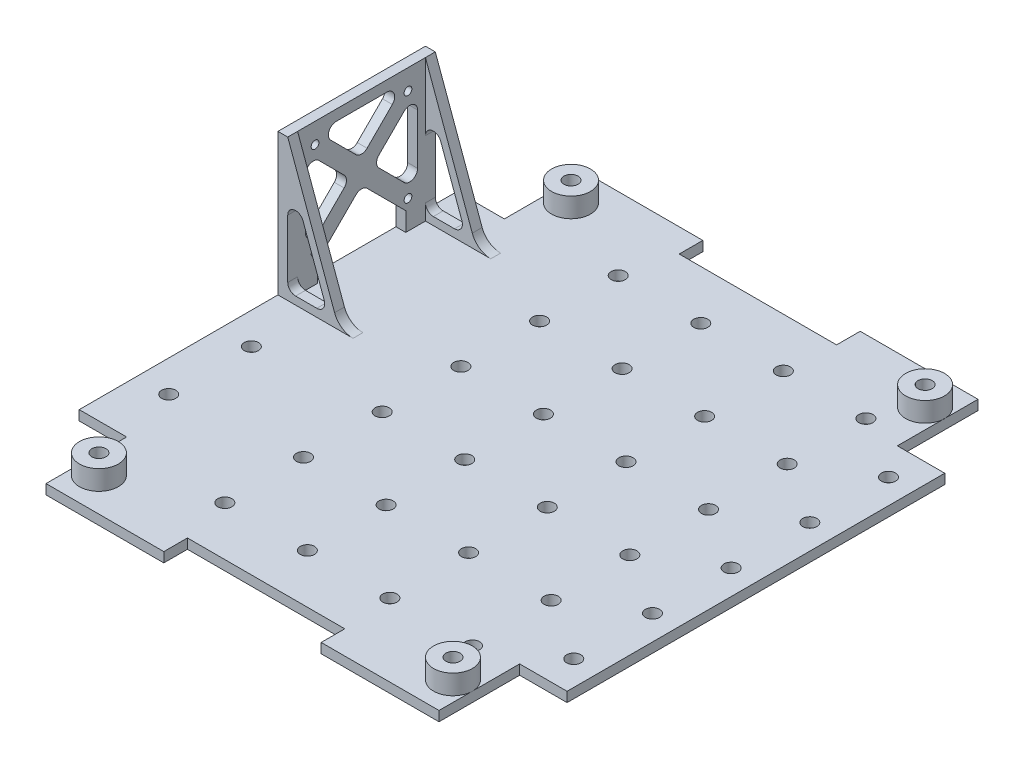
SolidWorks part; units mm, degrees
ref_plane "Front Plane" through (0, 0, 0) normal (0, 0, 1) x (1, 0, 0)
ref_plane "Top Plane" through (0, 0, 0) normal (0, 1, 0) x (1, 0, 0)
ref_plane "Right Plane" through (0, 0, 0) normal (1, 0, 0) x (0, 0, -1)
sketch "Sketch1" plane through (0, 0, 0) normal (0, 1, 0) x (1, 0, 0)
  line L0 (-25.4, 86.995) -> (-63.4314, 86.995)
  line L1 (-88.9, -101.6) -> (88.9, -101.6) construction
  line L2 (101.6, -88.9) -> (101.6, 88.9) construction
  line L3 (88.9, 101.6) -> (-88.9, 101.6) construction
  line L4 (-78.74, -60.96) -> (-63.4314, -60.96)
  line L5 (-63.4314, -60.96) -> (-63.4314, -86.995)
  line L6 (-63.4314, -86.995) -> (-25.4, -86.995)
  line L7 (63.4314, -86.995) -> (63.4314, -60.96)
  line L8 (63.4314, -60.96) -> (78.74, -60.96)
  line L9 (78.74, -60.96) -> (78.74, -25.4)
  line L10 (78.74, 60.96) -> (63.4314, 60.96)
  line L11 (63.4314, 60.96) -> (63.4314, 86.995)
  line L12 (63.4314, 86.995) -> (25.4, 86.995)
  line L13 (-63.4314, 86.995) -> (-63.4314, 60.96)
  line L14 (-63.4314, 60.96) -> (-78.74, 60.96)
  line L15 (-78.74, 60.96) -> (-78.74, 25.4)
  line L16 (-78.74, -25.4) -> (-78.74, -60.96)
  line L17 (-78.74, -25.4) -> (-71.12, -25.4)
  line L19 (-78.74, 25.4) -> (-71.12, 25.4)
  line L20 (-71.12, -25.4) -> (-71.12, 25.4)
  line L22 (-25.4, 86.995) -> (-25.4, 79.375)
  line L23 (-25.4, 79.375) -> (25.4, 79.375)
  line L24 (25.4, 86.995) -> (25.4, 79.375)
  line L25 (78.74, 25.4) -> (71.12, 25.4)
  line L27 (78.74, -25.4) -> (71.12, -25.4)
  line L28 (71.12, 25.4) -> (71.12, -25.4)
  line L30 (25.4, -86.995) -> (25.4, -79.375)
  line L31 (25.4, -79.375) -> (-25.4, -79.375)
  line L32 (-25.4, -86.995) -> (-25.4, -79.375)
  line L33 (78.74, 25.4) -> (78.74, 60.96)
  line L34 (25.4, -86.995) -> (63.4314, -86.995)
  line L35 (-101.6, 88.9) -> (-101.6, -88.9) construction
  arc A0 (88.9, -101.6) -> (101.6, -88.9) centre (88.9, -88.9) ccw construction
  arc A1 (-101.6, -88.9) -> (-88.9, -101.6) centre (-88.9, -88.9) ccw construction
  arc A2 (101.6, 88.9) -> (88.9, 101.6) centre (88.9, 88.9) ccw construction
  arc A3 (-101.6, 88.9) -> (-88.9, 101.6) centre (-88.9, 88.9) cw construction
  circle A4 centre (-57.15, 76.2) radius 2.286
  circle A5 centre (57.15, 76.2) radius 2.286
  circle A6 centre (57.15, -76.2) radius 2.286
  circle A7 centre (-57.15, -76.2) radius 2.286
  point P3 (0, 101.6)
  point P5 (101.6, 0)
  point P13 (101.6, 101.6)
  point P16 (-101.6, 101.6)
  point P38 (-71.12, 0)
  point P55 (0, -79.375)
  point P56 (0, 79.375)
  point P57 (71.12, 0)
  dimension "D2" = 12.7
  dimension "D11" = 4.572
  dimension "D8" = 44.45
  dimension "D1" = 203.2
  dimension "D3" = 203.2
  dimension "D4" = 22.86
  dimension "D5" = 15.3086
  dimension "D6" = 35.56
  dimension "D7" = 173.99
  dimension "D12" = 50.8
  dimension "D13" = 25.4
  dimension "D14" = 44.45
  dimension "D15" = 25.4
  dimension "D18" = 7.62
extrude "Main Body" add sketch "Sketch1" along normal blind 3.175
sketch "Sketch34" plane through (0, 3.175, 0) normal (0, 1, 0) x (1, 0, 0)
  line L0 (78.74, 25.4) -> (78.74, -25.4)
  line L1 (-78.74, 25.4) -> (-78.74, -25.4)
  line L28 (-78.74, -25.4) -> (-78.74, -60.96)
  line L29 (-78.74, -60.96) -> (-63.4314, -60.96)
  line L30 (-63.4314, -60.96) -> (-63.4314, -86.995)
  line L31 (-63.4314, -86.995) -> (-25.4, -86.995)
  line L32 (-25.4, -86.995) -> (-25.4, -79.375)
  line L33 (-25.4, -79.375) -> (25.4, -79.375)
  line L34 (25.4, -79.375) -> (25.4, -86.995)
  line L35 (25.4, -86.995) -> (63.4314, -86.995)
  line L36 (63.4314, -86.995) -> (63.4314, -60.96)
  line L37 (63.4314, -60.96) -> (78.74, -60.96)
  line L38 (78.74, -60.96) -> (78.74, -25.4)
  line L39 (78.74, -25.4) -> (71.12, -25.4)
  line L40 (71.12, -25.4) -> (71.12, 25.4)
  line L41 (71.12, 25.4) -> (78.74, 25.4)
  line L42 (78.74, 25.4) -> (78.74, 60.96)
  line L43 (78.74, 60.96) -> (63.4314, 60.96)
  line L44 (63.4314, 60.96) -> (63.4314, 86.995)
  line L45 (63.4314, 86.995) -> (25.4, 86.995)
  line L46 (25.4, 86.995) -> (25.4, 79.375)
  line L47 (25.4, 79.375) -> (-25.4, 79.375)
  line L48 (-25.4, 79.375) -> (-25.4, 86.995)
  line L49 (-25.4, 86.995) -> (-63.4314, 86.995)
  line L50 (-63.4314, 86.995) -> (-63.4314, 60.96)
  line L51 (-63.4314, 60.96) -> (-78.74, 60.96)
  line L52 (-78.74, 60.96) -> (-78.74, 25.4)
  line L53 (-78.74, 25.4) -> (-71.12, 25.4)
  line L54 (-71.12, 25.4) -> (-71.12, -25.4)
  line L55 (-71.12, -25.4) -> (-78.74, -25.4)
  line L56 (-78.74, -25.4) -> (-78.74, -60.96)
  line L57 (-78.74, -60.96) -> (-63.4314, -60.96)
  line L58 (-63.4314, -60.96) -> (-63.4314, -86.995)
  line L59 (-63.4314, -86.995) -> (-25.4, -86.995)
  line L60 (-25.4, -86.995) -> (-25.4, -79.375)
  line L61 (-25.4, -79.375) -> (25.4, -79.375)
  line L62 (25.4, -79.375) -> (25.4, -86.995)
  line L63 (25.4, -86.995) -> (63.4314, -86.995)
  line L64 (63.4314, -86.995) -> (63.4314, -60.96)
  line L65 (63.4314, -60.96) -> (78.74, -60.96)
  line L66 (78.74, -60.96) -> (78.74, -25.4)
  line L67 (78.74, -25.4) -> (71.12, -25.4)
  line L68 (71.12, -25.4) -> (71.12, 25.4)
  line L69 (71.12, 25.4) -> (78.74, 25.4)
  line L70 (78.74, 25.4) -> (78.74, 60.96)
  line L71 (78.74, 60.96) -> (63.4314, 60.96)
  line L72 (63.4314, 60.96) -> (63.4314, 86.995)
  line L73 (63.4314, 86.995) -> (25.4, 86.995)
  line L74 (25.4, 86.995) -> (25.4, 79.375)
  line L75 (25.4, 79.375) -> (-25.4, 79.375)
  line L76 (-25.4, 79.375) -> (-25.4, 86.995)
  line L77 (-25.4, 86.995) -> (-63.4314, 86.995)
  line L78 (-63.4314, 86.995) -> (-63.4314, 60.96)
  line L79 (-63.4314, 60.96) -> (-78.74, 60.96)
  line L80 (-78.74, 60.96) -> (-78.74, 25.4)
  line L81 (-78.74, 25.4) -> (-71.12, 25.4)
  line L82 (-71.12, 25.4) -> (-71.12, -25.4)
  line L83 (-71.12, -25.4) -> (-78.74, -25.4)
  line M42 (78.74, -25.4) -> (71.12, -25.4)
  line M43 (71.12, -25.4) -> (71.12, 25.4)
  line M44 (71.12, 25.4) -> (78.74, 25.4)
  line M56 (-78.74, 25.4) -> (-71.12, 25.4)
  line M57 (-71.12, 25.4) -> (-71.12, -25.4)
  line M58 (-71.12, -25.4) -> (-78.74, -25.4)
  dimension "D1" = 0
extrude "Boss-Extrude3" add sketch "Sketch34" against normal up to surface (3.175 mm away) contours L1 M56 M58 M57 | L0 M44 M43 M42 up to face at (0, 0, 0)
sketch "Sketch3" plane through (0, 3.175, 0) normal (0, 1, 0) x (1, 0, 0)
  line L0 (50.7314, -50.8) -> (50.7314, 50.8) construction
  line L28 (-78.74, 60.96) -> (-78.74, -60.96)
  line L29 (-78.74, -60.96) -> (-63.4314, -60.96)
  line L30 (-63.4314, -60.96) -> (-63.4314, -86.995)
  line L31 (-63.4314, -86.995) -> (-25.4, -86.995)
  line L32 (-25.4, -86.995) -> (-25.4, -79.375)
  line L33 (-25.4, -79.375) -> (25.4, -79.375)
  line L34 (25.4, -79.375) -> (25.4, -86.995)
  line L35 (25.4, -86.995) -> (63.4314, -86.995)
  line L36 (63.4314, -86.995) -> (63.4314, -60.96)
  line L37 (63.4314, -60.96) -> (78.74, -60.96)
  line L38 (78.74, -60.96) -> (78.74, 60.96)
  line L43 (78.74, 60.96) -> (63.4314, 60.96)
  line L44 (63.4314, 60.96) -> (63.4314, 86.995)
  line L45 (63.4314, 86.995) -> (25.4, 86.995)
  line L46 (25.4, 86.995) -> (25.4, 79.375)
  line L47 (25.4, 79.375) -> (-25.4, 79.375)
  line L48 (-25.4, 79.375) -> (-25.4, 86.995)
  line L49 (-25.4, 86.995) -> (-63.4314, 86.995)
  line L50 (-63.4314, 86.995) -> (-63.4314, 60.96)
  line L51 (-63.4314, 60.96) -> (-78.74, 60.96)
  line L56 (-78.74, 60.96) -> (-78.74, -60.96)
  line L57 (-78.74, -60.96) -> (-63.4314, -60.96)
  line L58 (-63.4314, -60.96) -> (-63.4314, -86.995)
  line L59 (-63.4314, -86.995) -> (-25.4, -86.995)
  line L60 (-25.4, -86.995) -> (-25.4, -79.375)
  line L61 (-25.4, -79.375) -> (25.4, -79.375)
  line L62 (25.4, -79.375) -> (25.4, -86.995)
  line L63 (25.4, -86.995) -> (63.4314, -86.995)
  line L64 (63.4314, -86.995) -> (63.4314, -60.96)
  line L65 (63.4314, -60.96) -> (78.74, -60.96)
  line L66 (78.74, -60.96) -> (78.74, 60.96)
  line L71 (78.74, 60.96) -> (63.4314, 60.96)
  line L72 (63.4314, 60.96) -> (63.4314, 86.995)
  line L73 (63.4314, 86.995) -> (25.4, 86.995)
  line L74 (25.4, 86.995) -> (25.4, 79.375)
  line L75 (25.4, 79.375) -> (-25.4, 79.375)
  line L76 (-25.4, 79.375) -> (-25.4, 86.995)
  line L77 (-25.4, 86.995) -> (-63.4314, 86.995)
  line L78 (-63.4314, 86.995) -> (-63.4314, 60.96)
  line L79 (-63.4314, 60.96) -> (-78.74, 60.96)
  circle A0 centre (50.7314, 50.8) radius 1.5875
  circle A1 centre (50.7314, 0) radius 1.5875
  circle A2 centre (50.7314, -50.8) radius 1.5875
  dimension "D2" = 3.175
  dimension "D5" = 101.6
  dimension "D6" = 12.7
  dimension "D1" = 0
sketch "Sketch35" plane through (0, 3.175, 0) normal (0, 1, 0) x (1, 0, 0)
  line L20 (-78.74, 60.96) -> (-78.74, -60.96)
  line L21 (-78.74, -60.96) -> (-63.4314, -60.96)
  line L22 (-63.4314, -60.96) -> (-63.4314, -86.995)
  line L23 (-63.4314, -86.995) -> (-25.4, -86.995)
  line L24 (-25.4, -86.995) -> (-25.4, -79.375)
  line L25 (-25.4, -79.375) -> (25.4, -79.375)
  line L26 (25.4, -79.375) -> (25.4, -86.995)
  line L27 (25.4, -86.995) -> (63.4314, -86.995)
  line L28 (63.4314, -86.995) -> (63.4314, -60.96)
  line L29 (63.4314, -60.96) -> (78.74, -60.96)
  line L30 (78.74, -60.96) -> (78.74, 60.96)
  line L31 (78.74, 60.96) -> (63.4314, 60.96)
  line L32 (63.4314, 60.96) -> (63.4314, 86.995)
  line L33 (63.4314, 86.995) -> (25.4, 86.995)
  line L34 (25.4, 86.995) -> (25.4, 79.375)
  line L35 (25.4, 79.375) -> (-25.4, 79.375)
  line L36 (-25.4, 79.375) -> (-25.4, 86.995)
  line L37 (-25.4, 86.995) -> (-63.4314, 86.995)
  line L38 (-63.4314, 86.995) -> (-63.4314, 60.96)
  line L39 (-63.4314, 60.96) -> (-78.74, 60.96)
  line L40 (-78.74, 60.96) -> (-78.74, -60.96)
  line L41 (-78.74, -60.96) -> (-63.4314, -60.96)
  line L42 (-63.4314, -60.96) -> (-63.4314, -86.995)
  line L43 (-63.4314, -86.995) -> (-25.4, -86.995)
  line L44 (-25.4, -86.995) -> (-25.4, -79.375)
  line L45 (-25.4, -79.375) -> (25.4, -79.375)
  line L46 (25.4, -79.375) -> (25.4, -86.995)
  line L47 (25.4, -86.995) -> (63.4314, -86.995)
  line L48 (63.4314, -86.995) -> (63.4314, -60.96)
  line L49 (63.4314, -60.96) -> (78.74, -60.96)
  line L50 (78.74, -60.96) -> (78.74, 60.96)
  line L51 (78.74, 60.96) -> (63.4314, 60.96)
  line L52 (63.4314, 60.96) -> (63.4314, 86.995)
  line L53 (63.4314, 86.995) -> (25.4, 86.995)
  line L54 (25.4, 86.995) -> (25.4, 79.375)
  line L55 (25.4, 79.375) -> (-25.4, 79.375)
  line L56 (-25.4, 79.375) -> (-25.4, 86.995)
  line L57 (-25.4, 86.995) -> (-63.4314, 86.995)
  line L58 (-63.4314, 86.995) -> (-63.4314, 60.96)
  line L59 (-63.4314, 60.96) -> (-78.74, 60.96)
  circle A0 centre (-57.15, 76.2) radius 2.286 construction
  circle A1 centre (-57.15, -76.2) radius 2.286 construction
  circle A2 centre (57.15, -76.2) radius 2.286 construction
  circle A3 centre (57.15, 76.2) radius 2.286 construction
  circle A4 centre (-57.15, 76.2) radius 2.286
  circle A5 centre (-57.15, -76.2) radius 2.286
  circle A6 centre (57.15, -76.2) radius 2.286
  circle A7 centre (57.15, 76.2) radius 2.286
  circle A8 centre (-57.15, 76.2) radius 6.2814
  circle A9 centre (-57.15, -76.2) radius 6.2814
  circle A10 centre (57.15, -76.2) radius 6.2814
  circle A11 centre (57.15, 76.2) radius 6.2814
  circle M21 centre (57.15, -76.2) radius 2.286
  circle M22 centre (-57.15, 76.2) radius 2.286
  circle M43 centre (57.15, 76.2) radius 2.286
  circle M44 centre (-57.15, -76.2) radius 2.286
  dimension "D1" = 0
extrude "Boss-Extrude4" add sketch "Sketch35" along normal blind 6.35 contours A11 M43 | A10 M21 | A9 M44 | A8 M22
sketch "Sketch37" plane through (0, 3.175, 0) normal (0, 1, 0) x (1, 0, 0)
  line L2 (-63.4314, 60.96) -> (-78.74, 60.96) construction
  line L3 (-78.74, 60.96) -> (-78.74, -60.96) construction
  line L24 (-78.74, 60.96) -> (-78.74, -60.96)
  line L25 (-63.4314, 60.96) -> (-78.74, 60.96)
  line L27 (-78.74, 50.8) -> (-75.565, 50.8)
  line L28 (-78.74, 50.8) -> (-78.74, 3.175)
  line L29 (-78.74, 3.175) -> (-75.565, 3.175)
  line L30 (-75.565, 50.8) -> (-75.565, 3.175)
  dimension "D1" = 3.175
  dimension "D2" = 47.625
  dimension "D3" = 10.16
extrude "Boss-Extrude5" add sketch "Sketch37" along normal blind 45.72 contours L30 L27 L24 L29
sketch "Sketch39" plane through (0, 0, -3.175) normal (0, 0, 1) x (1, 0, 0)
  line L0 (-75.565, 48.895) -> (-58.9243, 3.175)
  line L1 (-58.9243, 3.175) -> (-75.565, 3.175)
  line L4 (-78.74, 3.175) -> (-75.565, 3.175)
  line L5 (-75.565, 3.175) -> (-75.565, 48.895)
  line L6 (-75.565, 48.895) -> (-78.74, 48.895)
  line L7 (-78.74, 48.895) -> (-78.74, 3.175)
  line L8 (-78.74, 3.175) -> (-75.565, 3.175)
  line L9 (-75.565, 3.175) -> (-75.565, 48.895)
  line L10 (-75.565, 48.895) -> (-78.74, 48.895)
  line L11 (-78.74, 48.895) -> (-78.74, 3.175)
  dimension "D2" = 20
  dimension "D1" = 0
sketch "Sketch40" plane through (-78.74, 0, 0) normal (-1, 0, 0) x (0, 0, 1)
  line L0 (-35.1429, 45.4525) -> (-18.8321, 45.4525)
  line L1 (-45.9875, 8.355) -> (-7.9875, 8.355)
  line L2 (-45.9875, 8.355) -> (-45.9875, 46.355)
  line L3 (-45.9875, 46.355) -> (-7.9875, 46.355)
  line L4 (-7.9875, 8.355) -> (-7.9875, 46.355)
  line L5 (-45.9875, 8.355) -> (-7.9875, 46.355) construction
  line L6 (-45.9875, 46.355) -> (-7.9875, 8.355) construction
  line L7 (-17.0361, 41.1164) -> (-25.1914, 32.9611)
  line L9 (-3.175, 48.895) -> (-3.175, 3.175) construction
  line L10 (-50.8, 5.815) -> (-3.175, 5.815)
  line L11 (-50.8, 48.895) -> (-3.175, 48.895) construction
  line L12 (-50.8, 48.895) -> (-50.8, 3.175) construction
  line L19 (-3.175, 5.815) -> (-3.175, 48.895)
  line L20 (-3.175, 48.895) -> (-50.8, 48.895)
  line L21 (-50.8, 48.895) -> (-50.8, 5.815)
  line L24 (-28.7836, 32.9611) -> (-36.9389, 41.1164)
  line L25 (-21.3814, 29.1511) -> (-13.2261, 37.3064)
  line L26 (-8.89, 35.5104) -> (-8.89, 19.1996)
  line L27 (-13.2261, 17.4036) -> (-21.3814, 25.5589)
  line L28 (-25.1914, 21.7489) -> (-12.7, 9.2575)
  line L29 (-12.7, 9.2575) -> (-41.275, 9.2575)
  line L30 (-41.275, 9.2575) -> (-28.7836, 21.7489)
  line L31 (-32.5936, 25.5589) -> (-40.7489, 17.4036)
  line L32 (-45.085, 19.1996) -> (-45.085, 35.5104)
  line L33 (-40.7489, 37.3064) -> (-32.5936, 29.1511)
  circle A0 centre (-41.9875, 42.355) radius 1.25
  circle A1 centre (-11.9875, 42.355) radius 1.25
  circle A2 centre (-11.9875, 12.355) radius 1.25
  circle A3 centre (-41.9875, 12.355) radius 1.25
  arc A4 (-13.2261, 37.3064) -> (-8.89, 35.5104) centre (-11.43, 35.5104) cw
  arc A5 (-8.89, 19.1996) -> (-13.2261, 17.4036) centre (-11.43, 19.1996) cw
  arc A6 (-21.3814, 29.1511) -> (-21.3814, 25.5589) centre (-19.5854, 27.355) ccw
  arc A7 (-18.8321, 45.4525) -> (-17.0361, 41.1164) centre (-18.8321, 42.9125) cw
  arc A8 (-25.1914, 32.9611) -> (-28.7836, 32.9611) centre (-26.9875, 34.7571) cw
  arc A9 (-35.1429, 45.4525) -> (-36.9389, 41.1164) centre (-35.1429, 42.9125) ccw
  arc A10 (-45.085, 35.5104) -> (-40.7489, 37.3064) centre (-42.545, 35.5104) cw
  arc A11 (-32.5936, 25.5589) -> (-32.5936, 29.1511) centre (-34.3896, 27.355) ccw
  arc A12 (-40.7489, 17.4036) -> (-45.085, 19.1996) centre (-42.545, 19.1996) cw
  arc A13 (-25.1914, 21.7489) -> (-28.7836, 21.7489) centre (-26.9875, 19.9529) ccw
  point P2 (-50.8, 27.355)
  point P6 (-26.9875, 27.355)
  point P13 (-26.9875, 48.895)
  point P15 (-11.9875, 42.355)
  point P16 (-11.9875, 12.355)
  point P17 (-41.9875, 42.355)
  point P18 (-41.9875, 12.355)
  point P29 (-26.9875, 45.4525)
  point P43 (-26.9875, 27.355)
  point P49 (-23.1775, 27.355)
  point P52 (-12.7, 45.4525)
  point P55 (-26.9875, 31.165)
  point P58 (-41.275, 45.4525)
  point P63 (-30.7975, 27.355)
  point P68 (-26.9875, 23.545)
  dimension "D4" = 2.5
  dimension "D9" = 2.54
  dimension "D2" = 38
  dimension "D3" = 4
  dimension "D5" = 0.9025
  dimension "D6" = 3.81
  dimension "D7" = 45
  dimension "D8" = 4
  dimension "D1" = 2.54
extrude "Cut-Extrude3" cut sketch "Sketch40" against normal up to surface (3.175 mm away) contours L25 A4 L26 A5 L27 A6 | L28 L29 L30 A13 | A2 | A3 | L31 A12 L32 A10 L33 A11 | L7 A8 L24 A9 L0 A7 | A1 | A0 up to face at (-75.565, 26.035, -26.9875)
sketch "Sketch48" plane through (-78.74, 0, 0) normal (-1, 0, 0) x (0, 0, 1)
  line L0 (-12.7, 9.2575) -> (-41.275, 9.2575) construction
  line L1 (-12.7, 9.2575) -> (-41.275, 9.2575)
  line L2 (-41.275, 9.2575) -> (-41.275, 3.175)
  line L3 (-41.275, 3.175) -> (-12.7, 3.175)
  line L4 (-12.7, 3.175) -> (-12.7, 9.2575)
  line L12 (-60.96, 0) -> (60.96, 0)
  line L13 (60.96, 0) -> (60.96, 3.175)
  line L14 (60.96, 3.175) -> (-3.175, 3.175)
  line L19 (-3.175, 3.175) -> (-3.175, 48.895)
  line L20 (-3.175, 48.895) -> (-50.8, 48.895)
  line L21 (-50.8, 48.895) -> (-50.8, 3.175)
  line L22 (-50.8, 3.175) -> (-60.96, 3.175)
  line L23 (-60.96, 3.175) -> (-60.96, 0)
  line L24 (-60.96, 0) -> (60.96, 0)
  line L25 (60.96, 0) -> (60.96, 3.175)
  line L26 (60.96, 3.175) -> (-3.175, 3.175)
  line L31 (-3.175, 3.175) -> (-3.175, 48.895)
  line L32 (-3.175, 48.895) -> (-50.8, 48.895)
  line L33 (-50.8, 48.895) -> (-50.8, 3.175)
  line L34 (-50.8, 3.175) -> (-60.96, 3.175)
  line L35 (-60.96, 3.175) -> (-60.96, 0)
  line M19 (-12.7, 9.2575) -> (-41.275, 9.2575)
  dimension "D1" = 0
extrude "Cut-Extrude6" cut sketch "Sketch48" against normal up to next contours L3 L4 L2 M19
sketch "Sketch49" plane through (0, 3.175, 0) normal (0, 1, 0) x (1, 0, 0)
  line L0 (-68.58, -15.5575) -> (-68.58, -42.2275) construction
  line L1 (-78.74, 3.175) -> (-78.74, -60.96) construction
  circle A0 centre (-68.58, -15.5575) radius 2.286
  circle A1 centre (-68.58, -42.2275) radius 2.286
  point P4 (-68.58, -28.8925)
  point P7 (-78.74, -28.8925)
  dimension "D1" = 4.572
  dimension "D2" = 26.67
  dimension "D3" = 10.16
extrude "Cut-Extrude7" cut sketch "Sketch49" against normal through all
extrude "Extrude-Thin1" add sketch "Sketch39" against normal blind 3.175 thin contours L0 L1
fillet "Fillet1" radius 2.54 3 edges at (-75.565, 41.4685, -4.7625) (-62.5518, 5.715, -4.7625) (-75.565, 5.715, -4.7625)
fillet "Fillet2" radius 6.35 1 edges at (-58.9243, 3.175, -4.7625)
ref_plane "Plane3" through (0, 0, -26.9875) normal (0, 0, -1) x (-1, 0, 0)
mirror "Mirror2" about plane through (0, 0, -26.9875) normal (0, 0, -1) of "Fillet2", "Extrude-Thin1", "Fillet1"
sketch "Sketch50" plane through (0, 3.175, 0) normal (0, 1, 0) x (1, 0, 0)
  line L0 (-29.21, 63.5) -> (-29.21, -63.5) construction
  line L1 (-29.21, -63.5) -> (50.7314, -63.5) construction
  line L2 (63.4314, -76.2) -> (63.4314, -60.96) construction
  line L3 (-25.4, -86.995) -> (-25.4, -79.375) construction
  circle A0 centre (-29.21, 63.5) radius 2.286
  circle A1 centre (-2.5629, 63.5) radius 2.286
  circle A2 centre (24.0843, 63.5) radius 2.286
  circle A3 centre (50.7314, 63.5) radius 2.286
  circle A4 centre (-2.5629, 38.1) radius 2.286
  circle A5 centre (24.0843, 38.1) radius 2.286
  circle A6 centre (50.7314, 38.1) radius 2.286
  circle A7 centre (-2.5629, 12.7) radius 2.286
  circle A8 centre (24.0843, 12.7) radius 2.286
  circle A9 centre (50.7314, 12.7) radius 2.286
  circle A10 centre (-2.5629, -12.7) radius 2.286
  circle A11 centre (24.0843, -12.7) radius 2.286
  circle A12 centre (50.7314, -12.7) radius 2.286
  circle A13 centre (-2.5629, -38.1) radius 2.286
  circle A14 centre (24.0843, -38.1) radius 2.286
  circle A15 centre (50.7314, -38.1) radius 2.286
  circle A16 centre (-2.5629, -63.5) radius 2.286
  circle A17 centre (24.0843, -63.5) radius 2.286
  circle A18 centre (50.7314, -63.5) radius 2.286
  circle A19 centre (-29.21, 38.1) radius 2.286
  circle A20 centre (-29.21, 12.7) radius 2.286
  circle A21 centre (-29.21, -12.7) radius 2.286
  circle A22 centre (-29.21, -38.1) radius 2.286
  circle A23 centre (-29.21, -63.5) radius 2.286
  circle A24 centre (70.7339, 50.8) radius 2.286
  circle A25 centre (70.7339, 25.4) radius 2.286
  circle A26 centre (70.7339, 0) radius 2.286
  circle A27 centre (70.7339, -25.4) radius 2.286
  circle A28 centre (70.7339, -50.8) radius 2.286
  point P2 (-29.21, 0)
  point P56 (70.7339, -48.8156)
  dimension "D3" = 4.572
  dimension "D8" = 12.7
  dimension "D4" = 12.7
  dimension "D5" = 3.81
  dimension "D6" = 127
  dimension "D9" = 12.7
  dimension "D10" = 20.0025
  dimension "D1" = 4
  dimension "D2" = 6
  dimension "D7" = 5
extrude "Cut-Extrude8" cut sketch "Sketch50" against normal through all
